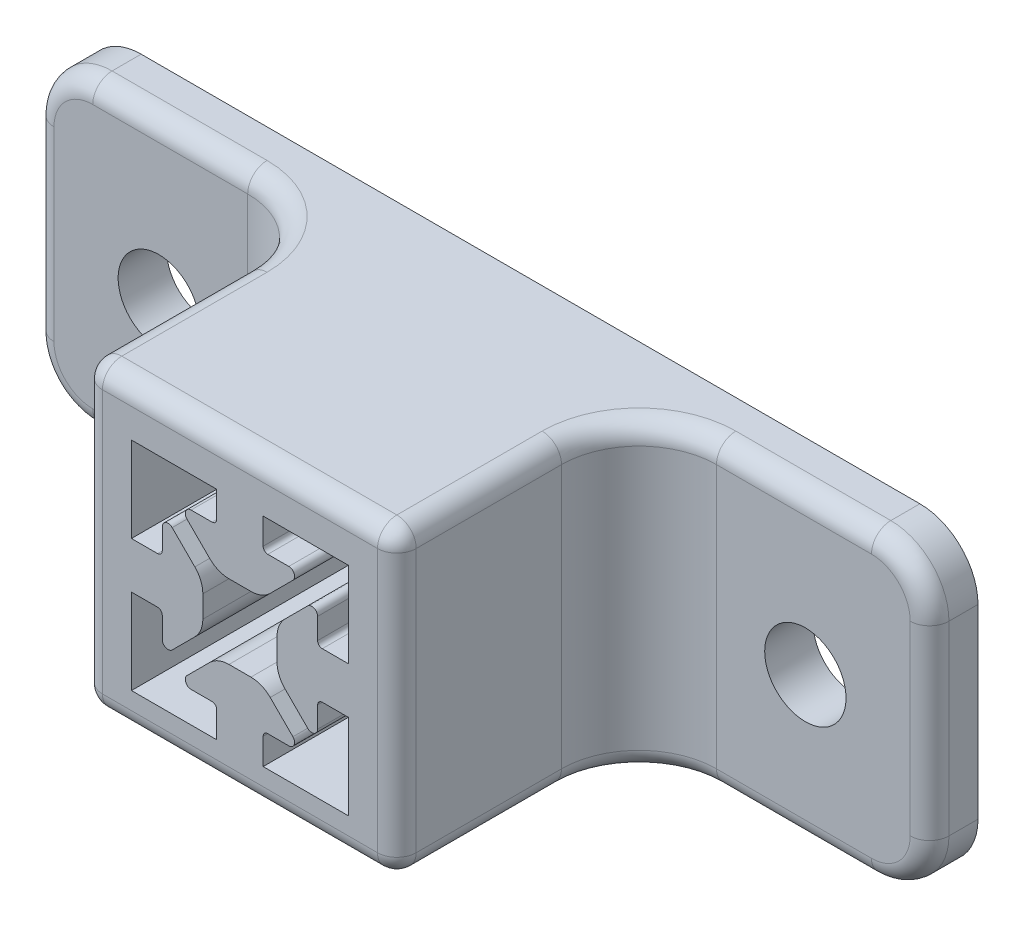
SolidWorks part; units mm, degrees
ref_plane "Front Plane" through (0, 0, 0) normal (0, 0, 1) x (1, 0, 0)
ref_plane "Top Plane" through (0, 0, 0) normal (0, 1, 0) x (1, 0, 0)
ref_plane "Right Plane" through (0, 0, 0) normal (1, 0, 0) x (0, 0, -1)
ref_plane "Plane1" through (0, 0, -585.7348) normal (0, 0, 1) x (1, 0, 0)
sketch "Sketch2" plane through (0, 0, -585.7348) normal (0, 0, 1) x (1, 0, 0)
  line L7 (-219.4843, 633.65) -> (-221.7534, 633.65) construction
  line L8 (-223.8747, 634.5287) -> (-226.2145, 636.8685) construction
  line L9 (-215.0232, 636.8685) -> (-217.363, 634.5287) construction
  line L10 (-217.7438, 638.2) -> (-215.5747, 638.2) construction
  line L11 (-218.0438, 639.2) -> (-218.0438, 638.5) construction
  line L12 (-223.1938, 638.5) -> (-223.1938, 639.2) construction
  line L13 (-225.663, 638.2) -> (-223.4938, 638.2) construction
  line L14 (-218.2238, 639.2) -> (-218.2238, 638.5)
  line L15 (-217.7438, 638.02) -> (-215.5747, 638.02)
  line L16 (-215.1505, 636.9957) -> (-217.4902, 634.656)
  line L17 (-219.4843, 633.83) -> (-221.7534, 633.83)
  line L18 (-223.7475, 634.656) -> (-226.0872, 636.9957)
  line L19 (-225.663, 638.02) -> (-223.4938, 638.02)
  line L20 (-223.0138, 638.5) -> (-223.0138, 639.2)
  line L21 (-220.6188, 630) -> (-220.6188, 642.8124) construction
  line L22 (-220.6188, 630) -> (-207.2782, 630) construction
  line L23 (-212.5988, 635.0441) -> (-212.5988, 632.875)
  line L24 (-215.9629, 633.1286) -> (-213.6231, 635.4684)
  line L25 (-216.7888, 628.8654) -> (-216.7888, 631.1346)
  line L26 (-212.5988, 627.125) -> (-212.5988, 624.9559)
  line L27 (-211.4188, 627.605) -> (-212.1188, 627.605)
  line L28 (-213.6231, 624.5316) -> (-215.9629, 626.8714)
  line L29 (-212.1188, 632.395) -> (-211.4188, 632.395)
  line L30 (-215.5747, 621.98) -> (-217.7438, 621.98)
  line L31 (-217.4902, 625.344) -> (-215.1505, 623.0043)
  line L32 (-221.7534, 626.17) -> (-219.4843, 626.17)
  line L33 (-223.4938, 621.98) -> (-225.663, 621.98)
  line L34 (-223.0138, 620.8) -> (-223.0138, 621.5)
  line L35 (-226.0872, 623.0043) -> (-223.7475, 625.344)
  line L36 (-218.2238, 621.5) -> (-218.2238, 620.8)
  line L37 (-228.6388, 624.9559) -> (-228.6388, 627.125)
  line L38 (-225.2748, 626.8714) -> (-227.6146, 624.5316)
  line L39 (-224.4488, 631.1346) -> (-224.4488, 628.8654)
  line L40 (-228.6388, 632.875) -> (-228.6388, 635.0441)
  line L41 (-229.8188, 632.395) -> (-229.1188, 632.395)
  line L42 (-227.6146, 635.4684) -> (-225.2748, 633.1286)
  line L43 (-229.1188, 627.605) -> (-229.8188, 627.605)
  line L44 (-231.8188, 618.8) -> (-231.8188, 627.605)
  line L46 (-223.0138, 620.8) -> (-223.0138, 618.8)
  line L47 (-223.0138, 618.8) -> (-231.8188, 618.8)
  line L49 (-231.8188, 641.2) -> (-223.0138, 641.2)
  line L50 (-229.8188, 627.605) -> (-231.8188, 627.605)
  line L51 (-229.8188, 632.395) -> (-231.8188, 632.395)
  line L52 (-231.8188, 632.395) -> (-231.8188, 641.2)
  line L54 (-209.4188, 618.8) -> (-209.4188, 627.605)
  line L55 (-211.4188, 627.605) -> (-209.4188, 627.605)
  line L56 (-211.4188, 632.395) -> (-209.4188, 632.395)
  line L57 (-209.4188, 632.395) -> (-209.4188, 641.2)
  line L59 (-218.2238, 618.8) -> (-209.4188, 618.8)
  line L60 (-223.0138, 639.2) -> (-223.0138, 641.2)
  line L61 (-218.2238, 639.2) -> (-218.2238, 641.2)
  line L62 (-218.2238, 641.2) -> (-209.4188, 641.2)
  line L64 (-236.8188, 646.2) -> (-204.4188, 646.2)
  line L65 (-236.8188, 646.2) -> (-236.8188, 615)
  line L66 (-236.8188, 615) -> (-204.4188, 615)
  line L67 (-204.4188, 646.2) -> (-204.4188, 615)
  line L68 (-218.2238, 620.8) -> (-218.2238, 618.8)
  arc A6 (-219.4843, 633.65) -> (-217.363, 634.5287) centre (-219.4843, 636.65) ccw construction
  arc A7 (-223.8747, 634.5287) -> (-221.7534, 633.65) centre (-221.7534, 636.65) ccw construction
  arc A8 (-215.0232, 636.8685) -> (-215.5747, 638.2) centre (-215.5747, 637.42) ccw construction
  arc A9 (-218.0438, 638.5) -> (-217.7438, 638.2) centre (-217.7438, 638.5) ccw construction
  arc A10 (-223.4938, 638.2) -> (-223.1938, 638.5) centre (-223.4938, 638.5) ccw construction
  arc A11 (-225.663, 638.2) -> (-226.2145, 636.8685) centre (-225.663, 637.42) ccw construction
  arc A12 (-218.2238, 638.5) -> (-217.7438, 638.02) centre (-217.7438, 638.5) ccw
  arc A13 (-215.1505, 636.9957) -> (-215.5747, 638.02) centre (-215.5747, 637.42) ccw
  arc A14 (-219.4843, 633.83) -> (-217.4902, 634.656) centre (-219.4843, 636.65) ccw
  arc A15 (-223.7475, 634.656) -> (-221.7534, 633.83) centre (-221.7534, 636.65) ccw
  arc A16 (-225.663, 638.02) -> (-226.0872, 636.9957) centre (-225.663, 637.42) ccw
  arc A17 (-223.4938, 638.02) -> (-223.0138, 638.5) centre (-223.4938, 638.5) ccw
  arc A18 (-212.5988, 635.0441) -> (-213.6231, 635.4684) centre (-213.1988, 635.0441) ccw
  arc A19 (-215.9629, 633.1286) -> (-216.7888, 631.1346) centre (-213.9688, 631.1346) ccw
  arc A20 (-216.7888, 628.8654) -> (-215.9629, 626.8714) centre (-213.9688, 628.8654) ccw
  arc A21 (-213.6231, 624.5316) -> (-212.5988, 624.9559) centre (-213.1988, 624.9559) ccw
  arc A22 (-212.1188, 627.605) -> (-212.5988, 627.125) centre (-212.1188, 627.125) ccw
  arc A23 (-212.5988, 632.875) -> (-212.1188, 632.395) centre (-212.1188, 632.875) ccw
  arc A24 (-215.5747, 621.98) -> (-215.1505, 623.0043) centre (-215.5747, 622.58) ccw
  arc A25 (-217.4902, 625.344) -> (-219.4843, 626.17) centre (-219.4843, 623.35) ccw
  arc A26 (-221.7534, 626.17) -> (-223.7475, 625.344) centre (-221.7534, 623.35) ccw
  arc A27 (-226.0872, 623.0043) -> (-225.663, 621.98) centre (-225.663, 622.58) ccw
  arc A28 (-223.0138, 621.5) -> (-223.4938, 621.98) centre (-223.4938, 621.5) ccw
  arc A29 (-217.7438, 621.98) -> (-218.2238, 621.5) centre (-217.7438, 621.5) ccw
  arc A30 (-228.6388, 624.9559) -> (-227.6146, 624.5316) centre (-228.0388, 624.9559) ccw
  arc A31 (-225.2748, 626.8714) -> (-224.4488, 628.8654) centre (-227.2688, 628.8654) ccw
  arc A32 (-224.4488, 631.1346) -> (-225.2748, 633.1286) centre (-227.2688, 631.1346) ccw
  arc A33 (-227.6146, 635.4684) -> (-228.6388, 635.0441) centre (-228.0388, 635.0441) ccw
  arc A34 (-229.1188, 632.395) -> (-228.6388, 632.875) centre (-229.1188, 632.875) ccw
  arc A35 (-228.6388, 627.125) -> (-229.1188, 627.605) centre (-229.1188, 627.125) ccw
  dimension "D5" = 5
  dimension "D6" = 5
  dimension "D7" = 5
  dimension "D1" = 0.18
  dimension "D2" = 4
extrude "Boss-Extrude1" add sketch "Sketch2" along normal blind 30
ref_plane "Plane2" through (-204.4188, 0, 0) normal (1, 0, 0) x (0, 0, -1)
sketch "Sketch3" plane through (-204.4188, 0, 0) normal (1, 0, 0) x (0, 0, -1)
  line L1 (585.7348, 646.2) -> (580.7348, 646.2)
  line L2 (585.7348, 646.2) -> (585.7348, 615)
  line L3 (585.7348, 615) -> (580.7348, 615)
  line L4 (580.7348, 646.2) -> (580.7348, 615)
  dimension "D1" = 5
ref_plane "Plane3" through (-220.6188, 0, 0) normal (1, 0, 0) x (0, 0, -1)
extrude "Boss-Extrude2" add sketch "Sketch3" along normal blind 30
ref_plane "Plane4" through (0, 0, -580.7348) normal (0, 0, 1) x (1, 0, 0)
sketch "Sketch4" plane through (0, 0, -580.7348) normal (0, 0, 1) x (1, 0, 0)
  line L4 (-183.0688, 584.25) -> (-183.0688, 675.75) construction
  line L5 (-191.4188, 675.75) -> (-191.4188, 584.25) construction
  line L6 (-183.0688, 584.25) -> (-183.0688, 675.75) construction
  line L7 (-191.4188, 675.75) -> (-191.4188, 584.25) construction
  line L8 (-191.4188, 630) -> (-183.0688, 630) construction
  circle A4 centre (-187.2438, 630) radius 4.1985
  dimension "D1" = 8.3969
extrude "Cut-Extrude1" cut sketch "Sketch4" against normal mid plane 30
mirror "Mirror6" about plane through (-220.6188, 0, 0) normal (1, 0, 0) of "Boss-Extrude2"
mirror "Mirror9" about plane through (-220.6188, 0, 0) normal (1, 0, 0) of "Cut-Extrude1"
fillet "Fillet6" radius 8 2 edges at (-236.8188, 630.6, -580.7348) (-204.4188, 630.6, -580.7348)
fillet "Fillet7" radius 6 4 edges at (-266.8188, 615, -583.2348) (-266.8188, 646.2, -583.2348) (-174.4188, 615, -583.2348) (-174.4188, 646.2, -583.2348)
fillet "Fillet8" radius 2 22 edges at (-204.4188, 630.6, -555.7348) (-220.6188, 646.2, -555.7348) (-239.162, 615, -578.3917) (-239.162, 646.2, -578.3917) (-202.0757, 615, -578.3917) (-202.0757, 646.2, -578.3917) (-188.4188, 615, -580.7348) (-252.8188, 615, -580.7348) (-266.8188, 630.6, -580.7348) (-252.8188, 646.2, -580.7348) (-265.0615, 644.4426, -580.7348) (-265.0615, 616.7574, -580.7348) (-188.4188, 646.2, -580.7348) (-174.4188, 630.6, -580.7348) (-176.1762, 644.4426, -580.7348) (-176.1762, 616.7574, -580.7348) (-236.8188, 630.6, -555.7348) (-236.8188, 646.2, -564.2348) (-204.4188, 646.2, -564.2348) (-204.4188, 615, -564.2348) (-236.8188, 615, -564.2348) (-220.6188, 615, -555.7348)
